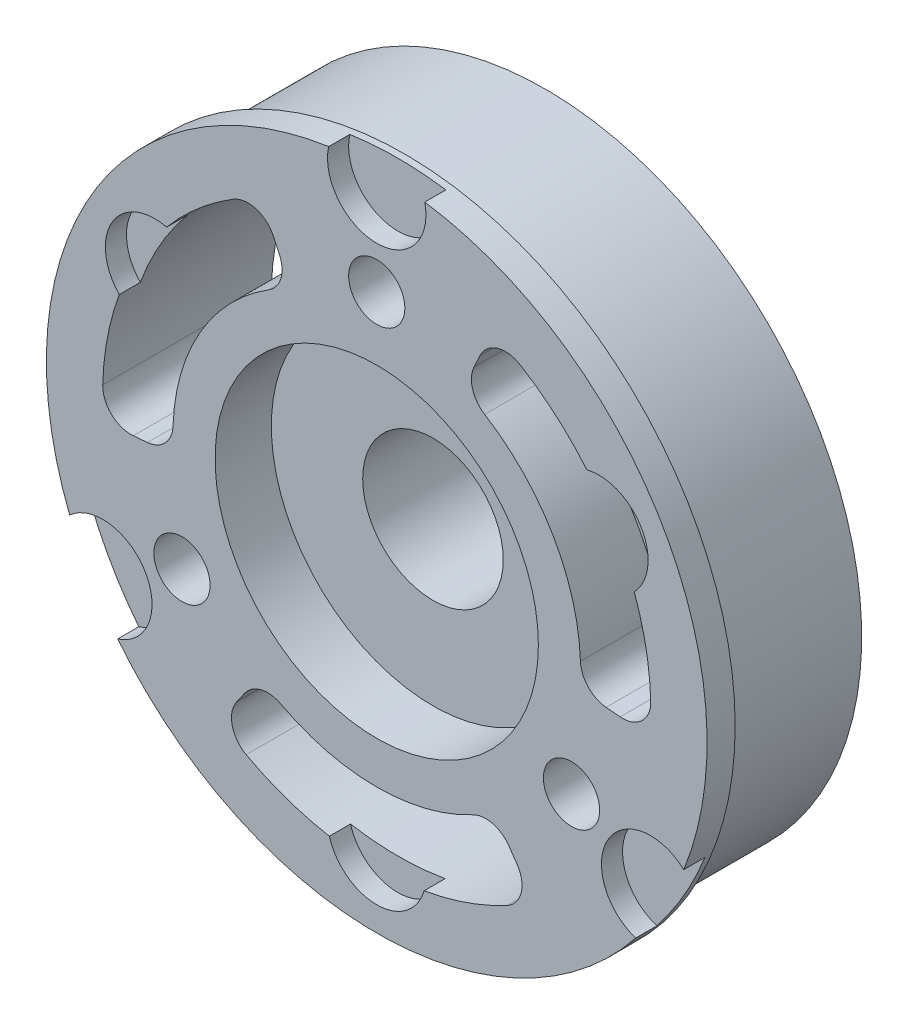
SolidWorks part; units mm, degrees
material "6061 合金"
ref_plane "前视基准面" through (0, 0, 0) normal (0, 0, 1) x (1, 0, 0)
ref_plane "上视基准面" through (0, 0, 0) normal (0, 1, 0) x (1, 0, 0)
ref_plane "右视基准面" through (0, 0, 0) normal (1, 0, 0) x (0, 0, -1)
sketch "草图1" plane through (0, 0, 0) normal (0, 0, 1) x (1, 0, 0)
  circle A0 centre (0, 0) radius 23.5
  dimension "D1" = 47
extrude "凸台-拉伸1" add sketch "草图1" along normal blind 2
sketch "草图2" plane through (0, 0, 0) normal (0, 0, -1) x (-1, 0, 0)
  circle A0 centre (0, 0) radius 22.5
  dimension "D1" = 45
extrude "凸台-拉伸2" add sketch "草图2" along normal blind 10
sketch "草图3" plane through (0, 0, -10) normal (0, 0, -1) x (-1, 0, 0)
  circle A0 centre (0, 0) radius 16 construction
  circle A1 centre (0, 16) radius 2
  circle A2 centre (13.8564, -8) radius 2
  circle A3 centre (-13.8564, -8) radius 2
  point P12 (0, 0)
  dimension "D1" = 32
  dimension "D2" = 4
  dimension "D3" = 3
extrude "切除-拉伸1" cut sketch "草图3" against normal blind 14
sketch "草图5" plane through (0, 0, -10) normal (0, 0, -1) x (-1, 0, 0)
  circle A0 centre (0, 0) radius 5
  dimension "D1" = 10
extrude "切除-拉伸2" cut sketch "草图5" against normal blind 14
sketch "草图6" plane through (0, 0, -10) normal (0, 0, -1) x (-1, 0, 0)
  line L0 (0, 0) -> (0, 29.4182) construction
  line L1 (0, 0) -> (12.6181, 27.0597)
  line L2 (0, 0) -> (17.1253, -24.4574)
  line L3 (0, 0) -> (13.8564, -8) construction
  line L4 (0, 0) -> (26.1327, -2.2863)
  line L5 (0, 0) -> (-15.0464, -21.4884)
  line L6 (0, 0) -> (-29.7434, -2.6022)
  line L7 (0, 0) -> (-11.0864, 23.7748)
  circle A0 centre (0, 0) radius 14.5
  circle A1 centre (0, 0) radius 19.5
  point P16 (0, 0)
  dimension "D1" = 29
  dimension "D2" = 39
  dimension "D3" = 25
  dimension "D4" = 25
  dimension "D5" = 3
extrude "切除-拉伸3" cut sketch "草图6" against normal blind 14 contours L4 A1 L1 A0 | L5 A1 L2 A0 | L7 A1 L6 A0
fillet "圆角1" radius 2 12 edges at (8.3169, -11.8777, -4) (11.1847, -15.9735, -4) (6.128, 13.1415, -4) (14.4448, -1.2638, -4) (19.4258, -1.6995, -4) (8.2411, 17.673, -4) (-11.1847, -15.9735, -4) (-8.3169, -11.8777, -4) (-19.4258, -1.6995, -4) (-14.4448, -1.2638, -4) (-6.128, 13.1415, -4) (-8.2411, 17.673, -4)
sketch "草图7" plane through (0, 0, 2) normal (0, 0, 1) x (1, 0, 0)
  line L0 (0, 0) -> (19.4856, -11.25) construction
  line L1 (19.4856, -11.25) -> (0, 22.5) construction
  line L2 (0, 0) -> (15.805, 9.125) construction
  circle A0 centre (0, 0) radius 22.5 construction
  circle A1 centre (0, 22.5) radius 3.5
  circle A2 centre (19.4856, -11.25) radius 3.5
  circle A3 centre (-19.4856, -11.25) radius 3.5
  circle A4 centre (0, 0) radius 18.25 construction
  circle A5 centre (15.805, 9.125) radius 3.5
  circle A6 centre (0, -18.25) radius 3.5
  circle A7 centre (-15.805, 9.125) radius 3.5
  point P11 (0, 0)
  point P19 (0, 0)
  dimension "D1" = 45
  dimension "D2" = 7
  dimension "D4" = 36.5
  dimension "D5" = 7
  dimension "D3" = 3
  dimension "D6" = 3
extrude "切除-拉伸4" cut sketch "草图7" against normal blind 1.5
sketch "草图8" plane through (0, 0, 2) normal (0, 0, 1) x (1, 0, 0)
  circle A0 centre (0, 0) radius 11.5
  dimension "D1" = 23
extrude "切除-拉伸5" cut sketch "草图8" against normal blind 4
